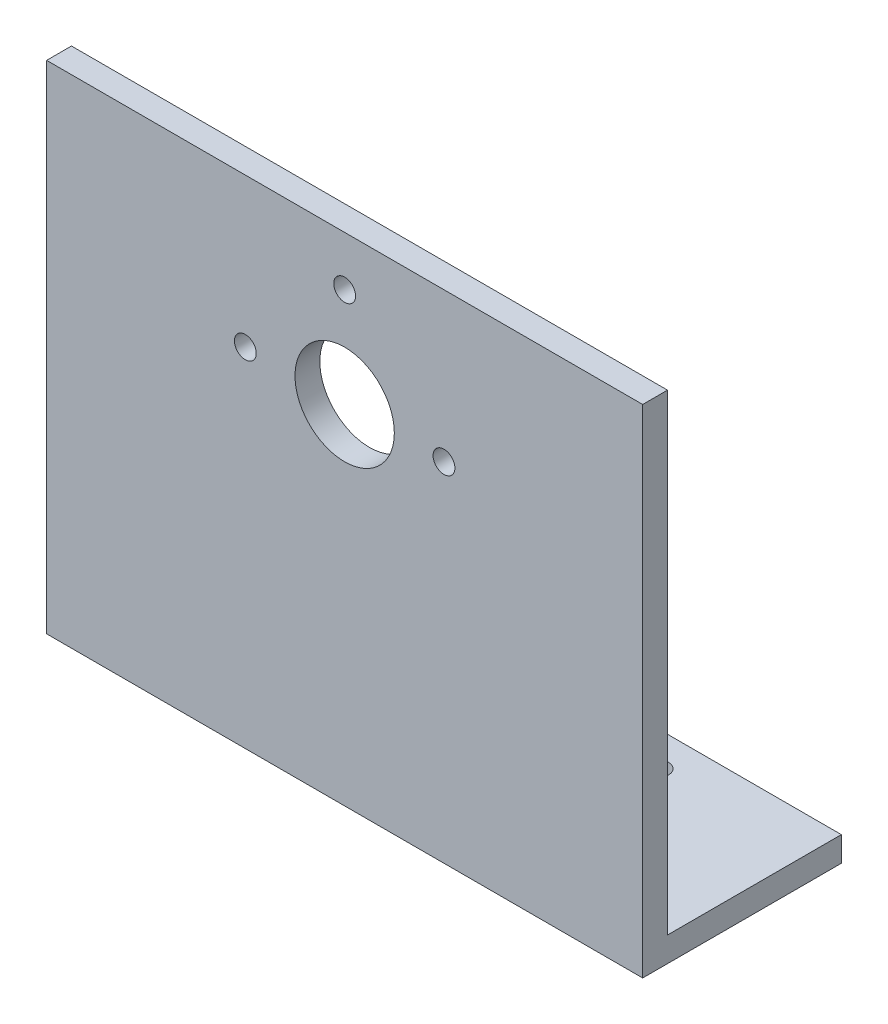
SolidWorks part; units mm, degrees
ref_plane "Front Plane" through (0, 0, 0) normal (0, 0, 1) x (1, 0, 0)
ref_plane "Top Plane" through (0, 0, 0) normal (0, 1, 0) x (1, 0, 0)
ref_plane "Right Plane" through (0, 0, 0) normal (1, 0, 0) x (0, 0, -1)
sketch "Sketch1" plane through (0, 0, 0) normal (0, 0, 1) x (1, 0, 0)
  line L1 (38.1, 19.05) -> (-38.1, 19.05)
  line L2 (38.1, 19.05) -> (38.1, -44.45)
  line L3 (38.1, -44.45) -> (-38.1, -44.45)
  line L4 (-38.1, 19.05) -> (-38.1, -44.45)
  circle A0 centre (0, 0) radius 6.35
  circle A1 centre (0, 12.7) radius 1.397
  circle A2 centre (-12.7, 0) radius 1.397
  circle A3 centre (12.7, 0) radius 1.397
  point P0 (0, 0)
extrude "Boss-Extrude1" add sketch "Sketch1" along normal blind 3.175
sketch "Sketch2" plane through (0, 0, 0) normal (0, 0, -1) x (-1, 0, 0)
  line L0 (38.1, 19.05) -> (38.1, -44.45) construction
  line L1 (-38.1, -44.45) -> (38.1, -44.45)
  line L2 (-38.1, -44.45) -> (-38.1, -41.275)
  line L3 (-38.1, -41.275) -> (38.1, -41.275)
  line L4 (38.1, -44.45) -> (38.1, -41.275)
extrude "Boss-Extrude2" add sketch "Sketch2" along normal blind 22.225
sketch "Sketch3" plane through (0, -41.275, 0) normal (0, 1, 0) x (1, 0, 0)
  circle A0 centre (-19.05, 17.78) radius 1.397
  circle A1 centre (19.05, 17.78) radius 1.397
extrude "Cut-Extrude1" cut sketch "Sketch3" against normal blind 3175
